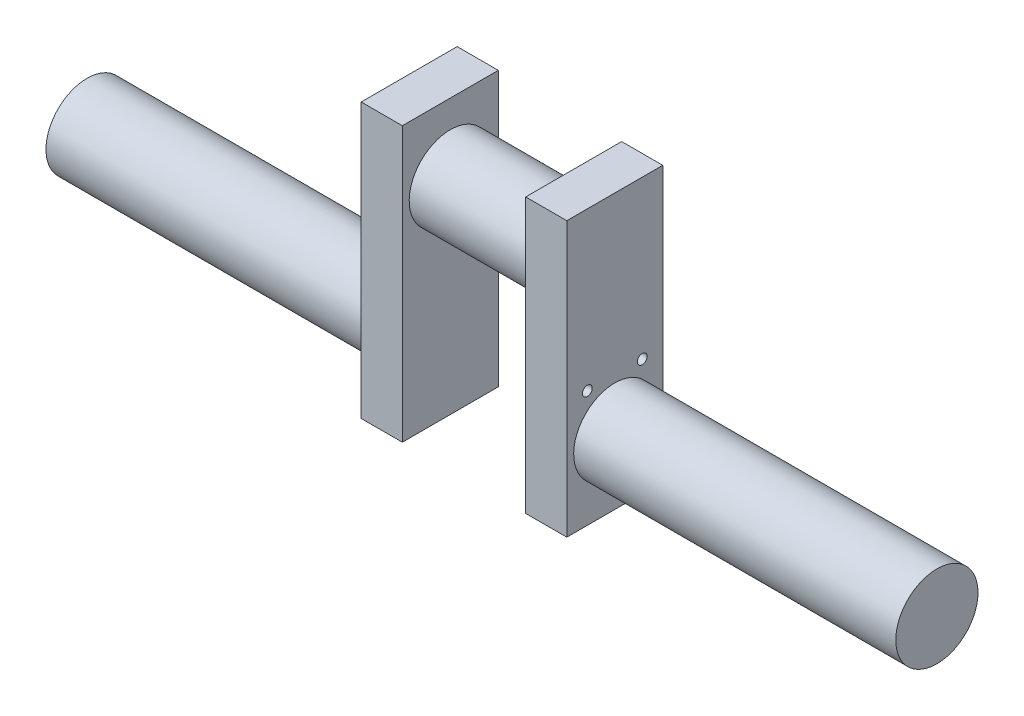
SolidWorks part; units mm, degrees
ref_plane "Front Plane" through (0, 0, 0) normal (0, 0, 1) x (1, 0, 0)
ref_plane "Top Plane" through (0, 0, 0) normal (0, 1, 0) x (1, 0, 0)
ref_plane "Right Plane" through (0, 0, 0) normal (1, 0, 0) x (0, 0, -1)
sketch "Sketch2" plane through (0, 0, 0) normal (0, 0, 1) x (1, 0, 0)
  line L0 (-25.0702, 0) -> (25.0069, 0) construction
  line L1 (0, 15.4473) -> (0, -14.3078) construction
  line L2 (-14.2875, 50.8242) -> (-14.2875, -12.6758)
  line L3 (-23.8125, 50.8242) -> (-23.8125, -12.6758)
  line L4 (-23.8125, 50.8242) -> (-14.2875, 50.8242)
  line L5 (-14.2875, -12.6758) -> (-23.8125, -12.6758)
  line L6 (14.2875, -12.6758) -> (23.8125, -12.6758)
  line L7 (23.8125, 50.8242) -> (14.2875, 50.8242)
  line L8 (23.8125, 50.8242) -> (23.8125, -12.6758)
  line L9 (14.2875, 50.8242) -> (14.2875, -12.6758)
  dimension "D1" = 28.575
  dimension "D3" = 63.5
  dimension "D2" = 9.525
extrude "Boss-Extrude1" add sketch "Sketch2" along normal blind 22.225
sketch "Sketch3" plane through (-14.2875, 0, 0) normal (1, 0, 0) x (0, 0, -1)
  line L1 (-22.225, 50.8242) -> (0, 50.8242) construction
  line L2 (0, 19.0742) -> (-22.225, 19.0742) construction
  line L3 (0, -12.6758) -> (0, 50.8242) construction
  line L4 (-22.225, -12.6758) -> (-22.225, 50.8242) construction
  circle A2 centre (-11.1125, 34.9492) radius 9.525
  point P4 (-11.1125, 44.4742)
  dimension "D1" = 6.35
  dimension "D2" = 9.525
sketch "Sketch4" plane through (23.8125, 0, 0) normal (1, 0, 0) x (0, 0, -1)
  circle A0 centre (-11.1125, 3.1992) radius 9.525
extrude "Boss-Extrude3" add sketch "Sketch3" along normal up to next
extrude "Boss-Extrude4" add sketch "Sketch4" along normal blind 74.6125
mirror "Mirror1" about plane through (0, 0, 0) normal (1, 0, 0) of "Boss-Extrude4"
hole_wizard "#43 (0.089) Diameter Hole1" positions "Sketch5" profile "Sketch6" hole size "#43" standard "ANSI Inch"
sketch "Sketch5" plane through (23.8125, 0, 0) normal (1, 0, 0) x (0, 0, -1)
  line L0 (-11.1125, 12.7242) -> (-11.1125, -6.3258) construction
  circle A2 centre (-11.1125, 34.9492) radius 9.525
  circle A3 centre (-11.1125, 34.9492) radius 9.525
  circle A6 centre (-11.1125, 3.1992) radius 9.525
  circle A7 centre (-11.1125, 3.1992) radius 9.525
  point P22 (-4.7625, 14.3117)
  point P28 (-17.4625, 14.3117)
  dimension "D2" = 11.1125
  dimension "D4" = 6.35
  dimension "D1" = 0
  dimension "D3" = 0
sketch "Sketch6" plane through (23.8125, 14.3117, 17.4625) normal (0, 1, 0) x (0, 0, -1)
  line L0 (0, 0) -> (0, 7.0292)
  line L1 (0, 7.0292) -> (1.1303, 6.35)
  line L2 (1.1303, 6.35) -> (1.1303, 0)
  line L5 (1.1303, 0) -> (0, 0)
  line L10 (0, 7.0292) -> (-1.1303, 6.35) construction
  line L11 (0, -6.35) -> (0, 107.95) construction
  dimension "Hole Dia." = 2.2606
  dimension "Hole Depth" = 6.35
  dimension "Drill Angle" = 118
